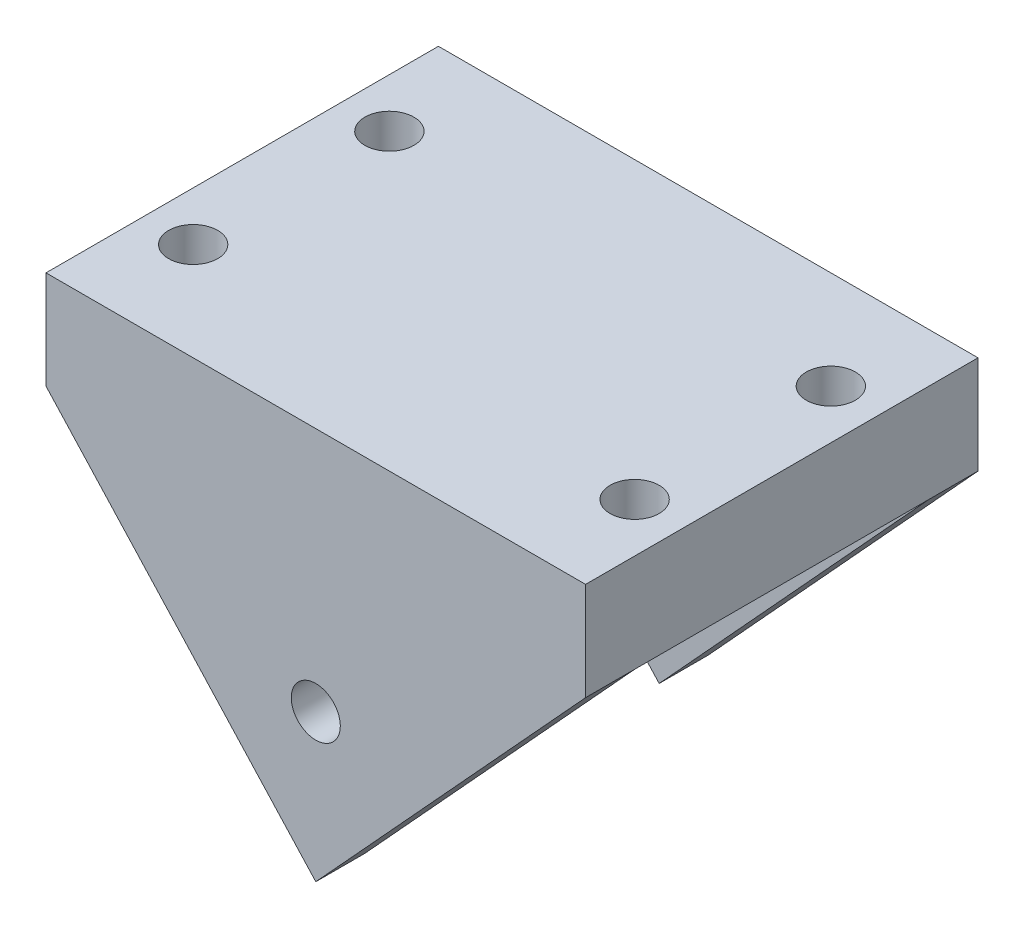
SolidWorks part; units mm, degrees
ref_plane "Front Plane" through (0, 0, 0) normal (0, 0, 1) x (1, 0, 0)
ref_plane "Top Plane" through (0, 0, 0) normal (0, 1, 0) x (1, 0, 0)
ref_plane "Right Plane" through (0, 0, 0) normal (1, 0, 0) x (0, 0, -1)
sketch "Sketch1" plane through (0, 0, 0) normal (0, 1, 0) x (1, 0, 0)
  line L1 (-55, 30) -> (55, 30)
  line L2 (-55, 30) -> (-55, -30)
  line L3 (-55, -30) -> (55, -30)
  line L4 (55, 30) -> (55, -30)
  line L5 (-55, 30) -> (55, -30) construction
  line L6 (-55, -30) -> (55, 30) construction
  point P0 (0, 0)
  dimension "D1" = 60
  dimension "D2" = 110
extrude "Boss-Extrude1" add sketch "Sketch1" along normal blind 20
sketch "Sketch3" plane through (0, 20, 0) normal (0, 1, 0) x (1, 0, 0)
  line L0 (0, -32.6793) -> (0, 38.6766) construction
  line L1 (-73.559, 0) -> (75.1615, 0) construction
  line L3 (-55, 30) -> (-55, -30) construction
  line L4 (55, 30) -> (-55, 30) construction
  circle A0 centre (-45, 20) radius 5
  circle A1 centre (45, 20) radius 5
  circle A2 centre (45, -20) radius 5
  circle A3 centre (-45, -20) radius 5
  dimension "D3" = 10
  dimension "D1" = 10
  dimension "D2" = 10
extrude "Cut-Extrude1" cut sketch "Sketch3" against normal blind 10
sketch "Sketch4" plane through (0, 0, 30) normal (0, 0, 1) x (1, 0, 0)
  line L0 (0, 25.7358) -> (0, -90.3015) construction
  line L1 (-55, 0) -> (0, -60)
  line L2 (0, -60) -> (55, 0)
  line L7 (-55, 0) -> (-55, 20)
  line L8 (-55, 20) -> (55, 20)
  line L9 (-55, 20) -> (55, 20) construction
  line L10 (55, 20) -> (55, 0)
  dimension "D1" = 60
extrude "Boss-Extrude2" add sketch "Sketch4" along normal blind 10
mirror "Mirror1" about plane through (0, 0, 0) normal (0, 0, 1) of "Boss-Extrude2"
sketch "Sketch5" plane through (0, 0, 40) normal (0, 0, 1) x (1, 0, 0)
  line L0 (0, -30) -> (0, 20) construction
  line L1 (55, 20) -> (-55, 20) construction
  circle A0 centre (0, -30) radius 5
  dimension "D1" = 10
  dimension "D2" = 50
extrude "Cut-Extrude2" cut sketch "Sketch5" against normal through all contours A0
